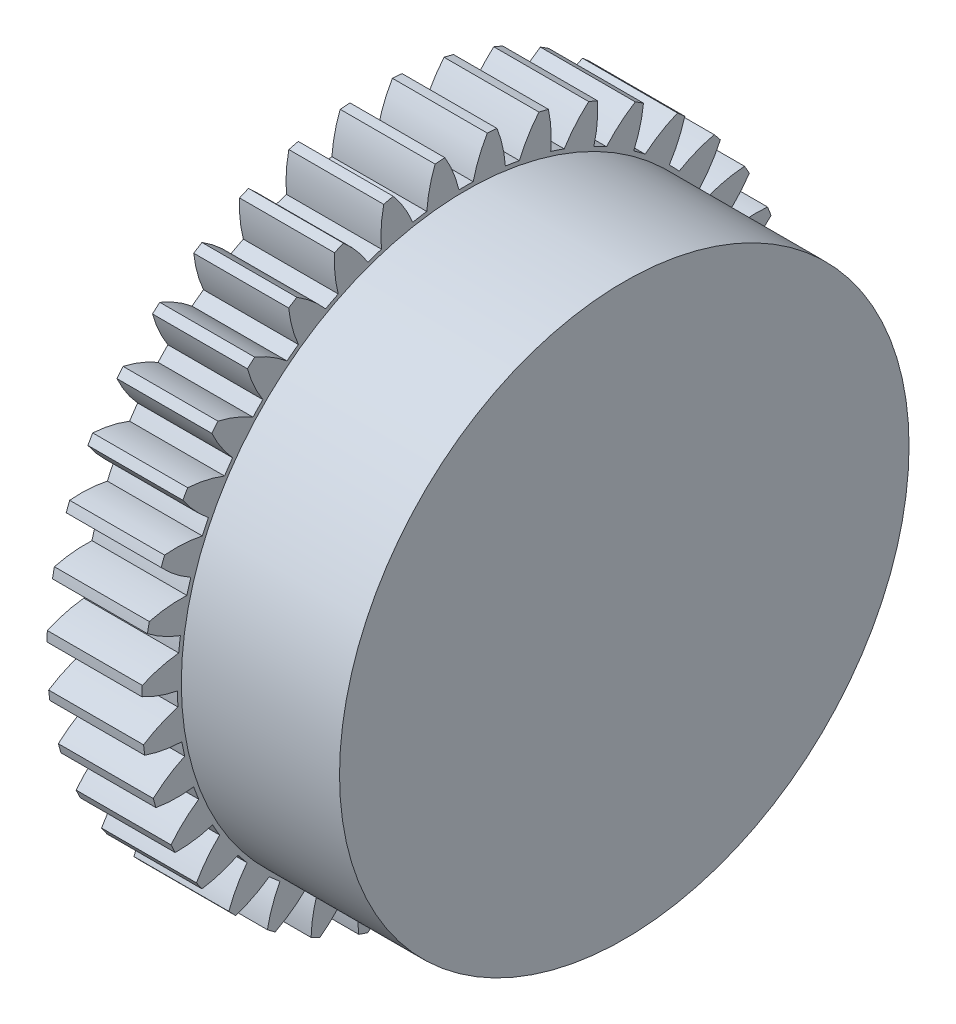
SolidWorks part; units mm, degrees
ref_plane "Plane1" through (0, 0, 0) normal (0, 0, 1) x (1, 0, 0)
ref_plane "Plane2" through (0, 0, 0) normal (0, 1, 0) x (1, 0, 0)
ref_plane "Plane3" through (0, 0, 0) normal (1, 0, 0) x (0, 0, -1)
other "Configuration Table"
sketch "HoldingSke" plane through (0, 0, 0) normal (0, 1, 0) x (1, 0, 0)
  line L0 (0, 0) -> (0.7771, -0.6293)
  line L1 (-15, 0) -> (100, 0) construction
  line L2 (0, 0) -> (-2.1039, 2.3779)
  line L3 (0, 0) -> (-11.863, 4.5341)
  line L4 (0, 0) -> (6.7114, 5.4348)
  line L5 (0, 0) -> (-46.8476, -17.4728)
  line L6 (0, 0) -> (-4.9738, -3.3558)
  line L7 (-2.1039, 2.3779) -> (8.6586, 51.2059)
  line L8 (-76.2, 54.61) -> (-72.9, 54.61)
  line L9 (-71.009, 38.7566) -> (-53.1078, 45.2721)
  line L10 (-76.2, 71.12) -> (104.1128, 71.12)
  line L11 (0, 0) -> (-6, 0)
  line L12 (-76.2, 101.6) -> (-76.162, 101.6)
  line L13 (24.9733, 27.94) -> (52.9518, 28.4284)
  line L14 (24.9733, 27.94) -> (24.9743, 27.94)
  line L15 (24.9733, 27.94) -> (100.4006, 29.5858)
  line L16 (-63.627, -1) -> (-12.827, -1)
  circle A0 centre (0, 0) radius 11
  circle A1 centre (0, 0) radius 18.249
  circle A2 centre (0, 0) radius 37.5
  circle A3 centre (0, 0) radius 11
  dimension "MHD" = 36.498
  dimension "Hub_dia" = 75
  dimension "Bore" = 22
  dimension "MBD" = 22
  dimension "Num_teeth" = 39
  dimension "Pitch" = 1
  dimension "Overall_len" = 50
  dimension "Show_teeth" = 39
  dimension "Thickness" = 6
  dimension "OAL" = 50.0001
  dimension "T_dim" = 3.3
  dimension "Ap" = 20
  dimension "H" = 19.05
  dimension "Pitch_radius" = 180.3128
  dimension "Width" = 6
  dimension "Backlash" = 0.038
  dimension "Addendum_fac" = 1
  dimension "Dedendum_fac" = 1.25
  dimension "Clearance_fac" = 0.25
  dimension "Dedendum_add" = 0.001
  dimension "Module" = 1
sketch "BasProSke" plane through (0, 0, 0) normal (0, 1, 0) x (1, 0, 0)
  line L0 (-10, 0) -> (60, 0) construction
  line L1 (0, 0) -> (0, 20.5)
  line L2 (0, 0) -> (6, 0)
  line L3 (6, 0) -> (6, 20.5)
  line L4 (6, 20.5) -> (0, 20.5)
  dimension "Thickness" = 6
  dimension "Diameter" = 41
revolve "Base-Revolve" add sketch "BasProSke" angle 360 about L0
sketch "TooCutSke" plane through (0, 0, 0) normal (1, 0, 0) x (0, 0, -1)
  line L1 (0, 0) -> (0, 107) construction
  line L2 (0, 0) -> (-0.8517, 19.4814) construction
  line L3 (0, 0) -> (-3.1361, 38.8471) construction
  line L4 (-0.8517, 19.4814) -> (-1.568, 19.4236) construction
  arc A0 (0.4501, 18.2434) -> (-0.4501, 18.2434) centre (0, 0) ccw
  arc A1 (1.358, 20.4804) -> (-1.358, 20.4804) centre (0, 0) ccw
  circle A2 centre (0, 0) radius 19.5 construction
  circle A3 centre (0, 0) radius 18.324 construction
  arc A4 (-0.4501, 18.2434) -> (-1.358, 20.4804) centre (-8.0443, 16.4638) ccw
  arc A5 (1.358, 20.4804) -> (0.4501, 18.2434) centre (8.0443, 16.4638) ccw
  dimension "Root_dia" = 36.498
  dimension "Overcut_dia" = 41.0508
  dimension "Pitch_dia" = 39
  dimension "Base_dia" = 36.648
  dimension "Flank_rad" = 7.8
  dimension "Half_ang" = 4.615
  dimension "Half_CT" = 0.7187
extrude "ToothCut" cut sketch "TooCutSke" along normal through all
fillet "Breaks" [suppressed] radius 0.02
fillet "RootFillets" [suppressed] radius 0.251
pattern_circular "TeethCuts" count 39 every 9.231 about axis through (-10, 0, 0) along (1, 0, 0) of "ToothCut", "RootFillets", "Breaks"
sketch "HubNeaOneSke" plane through (0, 0, 0) normal (-1, 0, 0) x (0, 0, 1)
  circle A0 centre (0, 0) radius 18.249
  dimension "Diameter" = 36.498
extrude "HubNearOne" [suppressed] add sketch "HubNeaOneSke" along normal blind 44.0001
sketch "HubNeaBotSke" plane through (0, 0, 0) normal (-1, 0, 0) x (0, 0, 1)
  circle A0 centre (0, 0) radius 18.249
  dimension "Diameter" = 36.498
extrude "HubNearBoth" [suppressed] add sketch "HubNeaBotSke" along normal blind 22
ref_plane "FarPln" through (6, 0, 0) normal (1, 0, 0) x (0, 0, -1)
sketch "HubFarSke" plane through (6, 0, 0) normal (1, 0, 0) x (0, 0, -1)
  circle A0 centre (0, 0) radius 18.249
  dimension "Diameter" = 36.498
extrude "HubFar" [suppressed] add sketch "HubFarSke" along normal blind 22
sketch "BorSke" plane through (0, 0, 0) normal (1, 0, 0) x (0, 0, -1)
  circle A0 centre (0, 0) radius 11
  dimension "Diameter" = 22
extrude "Bore" cut sketch "BorSke" along normal mid plane 100.0001
sketch "KeySke" plane through (0, 0, 0) normal (1, 0, 0) x (0, 0, -1)
  line L0 (-4, 0) -> (-4, 14.3)
  line L1 (-4, 14.3) -> (4, 14.3)
  line L2 (4, 14.3) -> (4, 0)
  line L3 (0, 0) -> (0, 34) construction
  line L4 (-4, 0) -> (4, 0)
  dimension "Offset" = 14.3
  dimension "Width" = 8
extrude "Keyway" [suppressed] cut sketch "KeySke" along normal mid plane 100.0001
pattern_circular "Keyway2" [suppressed] count 2 every 90 about axis through (-10, 0, 0) along (1, 0, 0)
sketch "Sketch2" plane through (6, 0, 0) normal (1, 0, 0) x (0, 0, -1)
  circle A0 centre (0, 0) radius 18
  dimension "D1" = 36
extrude "Boss-Extrude1" add sketch "Sketch2" along normal blind 10
equation "' \"Module@HoldingSke\" = 6.35"
equation "' \"Num_teeth@HoldingSke\" = 12"
equation "' \"Ap@HoldingSke\" =  20"
equation "' \"Ap@HoldingSke\" = 20"
equation "' \"Width@HoldingSke\" = 0.5 * 25.4"
equation "' \"Hub_dia@HoldingSke\"= 1 * 25.4"
equation "' \"Hub_dia@HoldingSke\" = 1 * 25.4"
equation "' \"Overall_len@HoldingSke\" = 1.0 * 25.4"
equation "' \"Bore@HoldingSke\" = 0.75 * 25.4"
equation "' \"T_dim@HoldingSke\" = 0.1 * 25.4"
equation "' \"Width@KeySke\" = 0.25 * 25.4"
equation "' \"Show_teeth@HoldingSke\" = 13"
equation "' \"Backlash@HoldingSke\" = 0.009 * 25.4"
equation "' \"Addendum_fac@HoldingSke\" = 1.0"
equation "' \"Dedendum_fac@HoldingSke\" = 1.25"
equation "' \"Dedendum_add@HoldingSke\" = 0.00005 * 25.4"
equation "' \"Clearance_fac@HoldingSke\" = 0.25"
equation "\"Pitch@HoldingSke\" = 1 / \"Module@HoldingSke\""
equation "\"Overcut_dia@TooCutSke\" = (\"Num_teeth@HoldingSke\" + 2 * \"Addendum_fac@HoldingSke\") / \"Pitch@HoldingSke\" + 0.002 * 25.4"
equation "\"Pitch_dia@TooCutSke\" = \"Num_teeth@HoldingSke\" / \"Pitch@HoldingSke\""
equation "\"Base_dia@TooCutSke\" = \"Num_teeth@HoldingSke\" / \"Pitch@HoldingSke\" * cos((\"Ap@HoldingSke\"  * 3.14159265 / 180))"
equation "\"Root_dia@TooCutSke\" = (\"Num_teeth@HoldingSke\" + 2) / \"Pitch@HoldingSke\" - 2 * (\"Addendum_fac@HoldingSke\" + \"Dedendum_fac@HoldingSke\") / \"Pitch@HoldingSke\" - \"Dedendum_add@HoldingSke\" * 2"
equation "\"Half_ang@TooCutSke\" = 180 / \"Num_teeth@HoldingSke\""
equation "\"Half_CT@TooCutSke\" = \"Num_teeth@HoldingSke\" / \"Pitch@HoldingSke\" * sin((3.14159265 / 2 / \"Num_teeth@HoldingSke\")) / 2 - 7 * \"Backlash@HoldingSke\" / 4"
equation "\"Flank_rad@TooCutSke\" = \"Num_teeth@HoldingSke\" / \"Pitch@HoldingSke\" / 5"
equation "\"Radius@RootFillets\" = \"Clearance_fac@HoldingSke\" / \"Pitch@HoldingSke\" + \"Dedendum_add@HoldingSke\""
equation "\"Break_rad@Breaks\" = 0.02 / \"Pitch@HoldingSke\""
equation "\"Thickness@HoldingSke\" = \"Width@HoldingSke\""
equation "\"OAL@HoldingSke\" = \"Thickness@HoldingSke\""
equation "\"MHD@HoldingSke\" = (\"Num_teeth@HoldingSke\" + 2) / \"Pitch@HoldingSke\" - 2 * (\"Addendum_fac@HoldingSke\" + \"Dedendum_fac@HoldingSke\")  / \"Pitch@HoldingSke\" - \"Dedendum_add@HoldingSke\" * 2"
equation "\"MBD@HoldingSke\" = (\"Num_teeth@HoldingSke\" + 2) / \"Pitch@HoldingSke\" - 2 * (\"Addendum_fac@HoldingSke\" + \"Dedendum_fac@HoldingSke\")  / \"Pitch@HoldingSke\" - \"Dedendum_add@HoldingSke\" * 2 - 0.002 * 25.4"
equation "\"MHD@HoldingSke\" = ((sgn( \"MHD@HoldingSke\" - \"Hub_dia@HoldingSke\" )-1)*( \"MHD@HoldingSke\" - \"Hub_dia@HoldingSke\" ))/-2+ \"Hub_dia@HoldingSke\""
equation "\"MBD@HoldingSke\" = ((sgn( \"MBD@HoldingSke\" - \"Bore@HoldingSke\" )-1)*( \"MBD@HoldingSke\" - \"Bore@HoldingSke\" ))/-2+ \"Bore@HoldingSke\""
equation "\"OAL@HoldingSke\" = ((sgn( \"OAL@HoldingSke\" - \"Overall_len@HoldingSke\" )+1)*( \"OAL@HoldingSke\" - \"Overall_len@HoldingSke\" ))/2 + \"Overall_len@HoldingSke\" + 0.000002 * 25.4"
equation "\"Num_teeth@TeethCuts\" = int( \"Show_teeth@HoldingSke\" ) + 1"
equation "\"Num_teeth@TeethCuts\" = ((sgn( \"Num_teeth@TeethCuts\" - \"Num_teeth@HoldingSke\" )-1)*( \"Num_teeth@TeethCuts\" - \"Num_teeth@HoldingSke\" ))/-2+ \"Num_teeth@HoldingSke\""
equation "\"Num_teeth@TeethCuts\" = ((sgn( \"Num_teeth@TeethCuts\" - 2.0)+1)*( \"Num_teeth@TeethCuts\" - 2.0))/2 +2.0"
equation "\"Angle@TeethCuts\" = 360.0 / \"Num_teeth@HoldingSke\""
equation "\"Diameter@BasProSke\" = (\"Num_teeth@HoldingSke\" + 2 * \"Addendum_fac@HoldingSke\") / \"Pitch@HoldingSke\""
equation "\"Thickness@BasProSke\"  = \"Thickness@HoldingSke\""
equation "' \"Fillet_rad@BasProSke\" =  \"Thickness@HoldingSke\" * 0.05"
equation "' \"Fillet_rad@BasProSke\" = \"Thickness@HoldingSke\" * 0.05"
equation "\"MHD@HoldingSke\" = ((sgn( \"MHD@HoldingSke\" - \"Root_dia@TooCutSke\" )-1)*( \"MHD@HoldingSke\" - \"Root_dia@TooCutSke\" ))/-2+ \"Root_dia@TooCutSke\""
equation "\"Diameter@HubNeaOneSke\" = \"MHD@HoldingSke\""
equation "\"Length@HubNearOne\" = \"OAL@HoldingSke\" - \"Thickness@BasProSke\""
equation "\"Diameter@HubNeaBotSke\" = \"MHD@HoldingSke\""
equation "\"Length@HubNearBoth\" = ( \"OAL@HoldingSke\" - \"Thickness@BasProSke\" ) / 2.0"
equation "\"Thickness@FarPln\" = \"Thickness@BasProSke\""
equation "\"Diameter@HubFarSke\" = \"MHD@HoldingSke\""
equation "\"Length@HubFar\" = ( \"OAL@HoldingSke\" - \"Thickness@BasProSke\" ) / 2.0"
equation "\"Diameter@BorSke\" = \"MBD@HoldingSke\""
equation "\"D1@Bore\" = \"OAL@HoldingSke\" * 2.0"
equation "\"D1@Keyway\" = \"OAL@HoldingSke\" * 2.0"
equation "\"Offset@KeySke\" = \"T_dim@HoldingSke\" + \"MBD@HoldingSke\" / 2.0"
